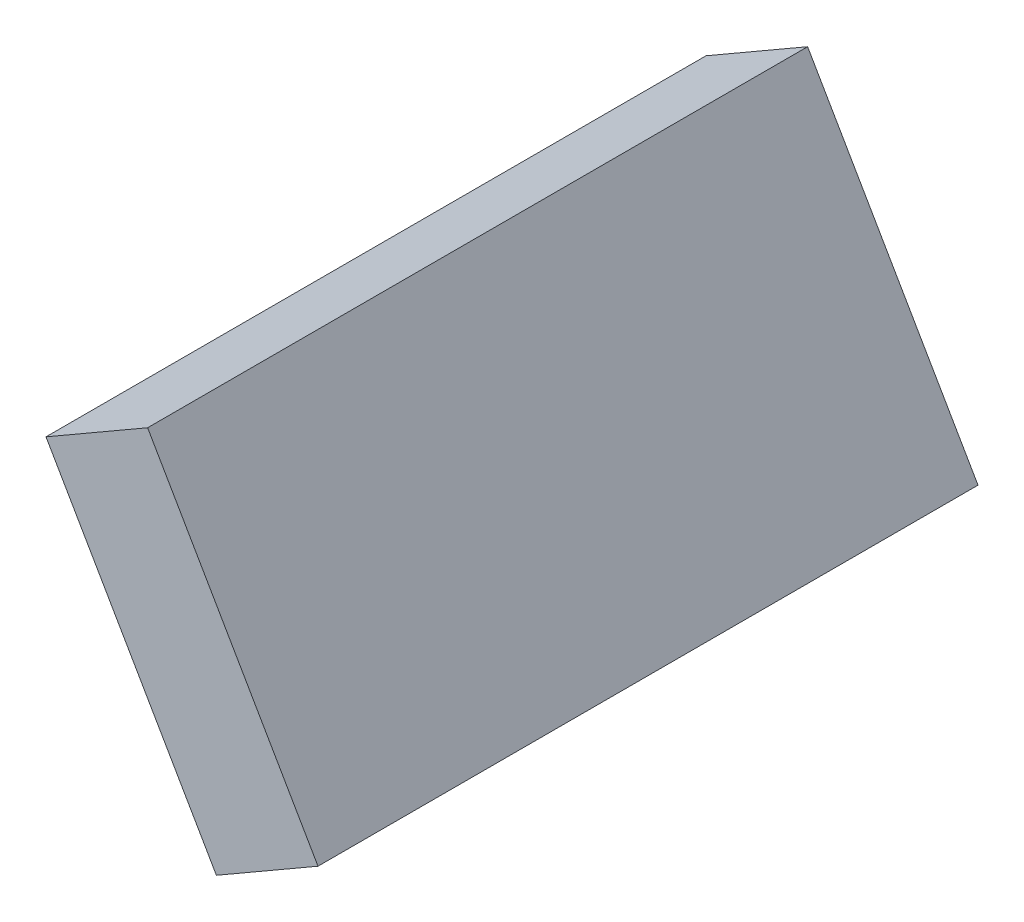
SolidWorks part; units mm, degrees
ref_plane "Front Plane" through (0, 0, 0) normal (0, 0, 1) x (1, 0, 0)
ref_plane "Top Plane" through (0, 0, 0) normal (0, 1, 0) x (1, 0, 0)
ref_plane "Right Plane" through (0, 0, 0) normal (1, 0, 0) x (0, 0, -1)
sketch "Sketch1" plane through (0, 0, 0) normal (0, 0, 1) x (1, 0, 0)
  line L0 (-647.4603, -317.6195) -> (-477.476, -23.1982)
  line L1 (-477.476, -23.1982) -> (-442.476, -23.1982)
  line L2 (-442.476, -23.1982) -> (-272.4917, -317.6195)
  line L3 (-272.4917, -317.6195) -> (-289.9917, -347.9304)
  line L4 (-289.9917, -347.9304) -> (-629.9603, -347.9304)
  line L5 (-629.9603, -347.9304) -> (-647.4603, -317.6195)
  line L16 (-459.8079, -231.5859) -> (-459.8079, -114.0541) construction
  circle A1 centre (-581.2092, -222.8693) radius 3.2
  circle A2 centre (-528.6492, -131.8327) radius 3.2
  circle A3 centre (-500.5777, -148.0115) radius 3.2
  circle A4 centre (-553.1368, -239.0465) radius 3.2
  circle A13 centre (-367.2942, -238.2091) radius 3.2
  circle A14 centre (-419.8542, -147.1725) radius 3.2
  circle A15 centre (-391.5457, -131.4121) radius 3.2
  circle A16 centre (-338.9857, -222.4487) radius 3.2
  circle A17 centre (-511.8008, -305.5304) radius 3.2
  circle A18 centre (-406.6805, -305.5304) radius 3.2
  circle A19 centre (-406.6806, -337.9304) radius 3.2
  circle A20 centre (-511.8006, -337.9304) radius 3.2
  circle A27 centre (-459.8079, -114.0541) radius 14
  circle A28 centre (-358.0223, -290.3519) radius 14
  circle A29 centre (-561.5935, -290.3519) radius 14
  point P6 (-526.8577, -193.5298)
  point P17 (-393.5776, -192.6927)
  point P20 (-459.8079, -217.9304)
  point P29 (-459.2405, -305.5304)
  point P61 (-511.8734, -202.181)
  dimension "D5" = 32.4
  dimension "D6" = 52.56
  dimension "D16" = 10
  dimension "D28" = 6.4
  dimension "D30" = 6.4
  dimension "D4" = 105.1182
  dimension "D7" = 105.12
  dimension "D8" = 32.4
  dimension "D9" = 10
  dimension "D10" = 42.4
  dimension "D11" = 52.56
  dimension "D12" = 110
  dimension "D13" = 10
  dimension "D14" = 105.12
  dimension "D15" = 110
  dimension "D17" = 32.4
  dimension "D18" = 130
  dimension "D19" = 105.12
  dimension "D20" = 10
  dimension "D21" = 42.4
  dimension "D22" = 10
  dimension "D23" = 10
  dimension "D24" = 339.9685
  dimension "D25" = 32.4
  dimension "D27" = 52.56
  dimension "D29" = 105.12
  dimension "D31" = 42.4
  dimension "D36" = 3
sketch "Sketch4" plane through (0, 0, 0) normal (0, 0, 1) x (1, 0, 0)
  line L6 (-448.3251, -177.8537) -> (-419.284, -228.0594)
  line L11 (-289.9917, -347.9304) -> (-629.9603, -347.9304) construction
  line L12 (-465.6456, -187.8537) -> (-448.3251, -177.8537)
  line L13 (-515.6456, -187.8537) -> (-498.3251, -177.8537)
  line L14 (-486.6045, -238.0594) -> (-469.284, -228.0594)
  line L17 (-515.6456, -187.8537) -> (-486.6045, -238.0594)
  line L18 (-498.3251, -177.8537) -> (-469.284, -228.0594)
  line L19 (-465.6456, -187.8537) -> (-436.6045, -238.0594)
  line L20 (-436.6045, -238.0594) -> (-419.284, -228.0594)
  circle A0 centre (-407.8463, -172.5859) radius 11
  circle A2 centre (-511.7694, -172.5859) radius 11
  circle A3 centre (-459.8079, -262.5859) radius 11
  point P6 (-459.8079, -202.5859)
  point P19 (-459.8079, -202.5859)
  point P21 (-459.8079, -182.9304)
  dimension "D5" = 60
  dimension "D6" = 103.923
  dimension "D3" = 22
  dimension "D7" = 3
  dimension "D4" = 58
  dimension "D2" = 60
  dimension "D8" = 2
  dimension "D9" = 20
  dimension "D11" = 165
extrude "Boss-Extrude2" add sketch "Sketch4" along normal blind 112.5 contours L18 L13 L17 L14
ref_plane "Plane1" through (-469.284, -228.0594, 0) normal (0.866, 0.5, 0) x (0, 0, -1)
